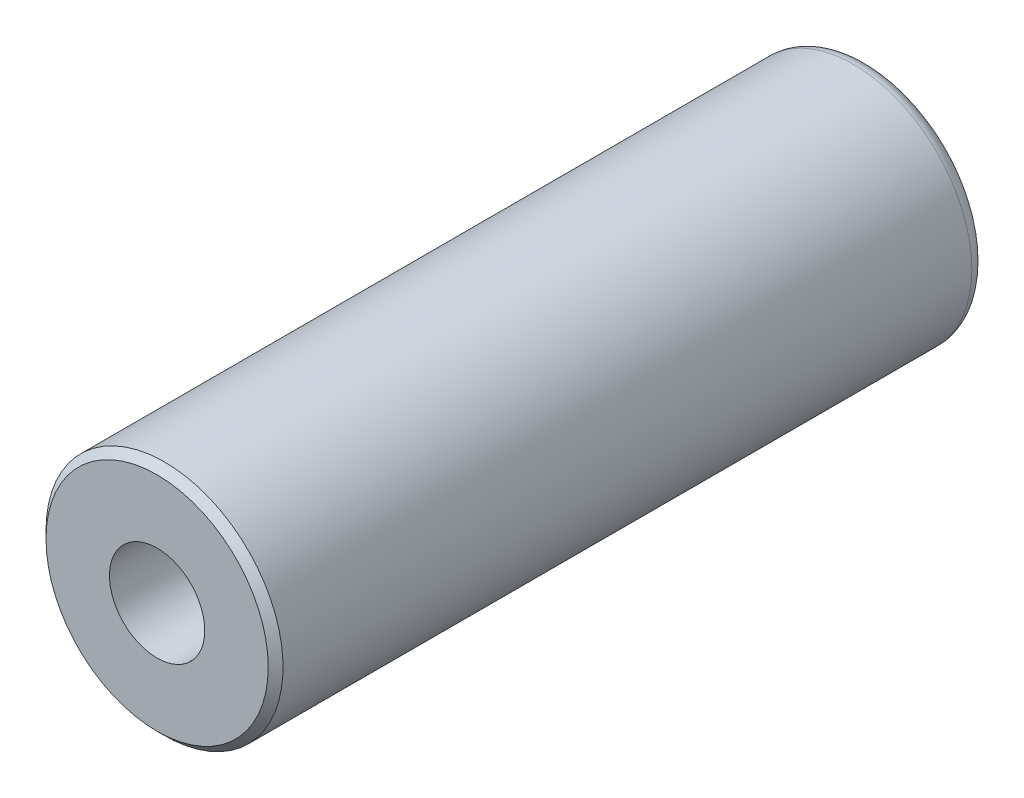
SolidWorks part; units mm, degrees
ref_plane "Front" through (0, 0, 0) normal (0, 0, 1) x (1, 0, 0)
ref_plane "Top" through (0, 0, 0) normal (0, 1, 0) x (1, 0, 0)
ref_plane "Right" through (0, 0, 0) normal (1, 0, 0) x (0, 0, -1)
sketch "Sketch1" plane through (0, 0, 0) normal (0, 0, 1) x (1, 0, 0)
  circle A0 centre (0, 0) radius 6.35
  dimension "D1" = 12.7
extrude "Extrude1" add sketch "Sketch1" along normal blind 38.1
hole_wizard "1/4-20 Tapped Hole1" positions "Sketch3" profile "Sketch2" tap size "1/4-20" standard "Ansi Inch"
sketch "Sketch3" plane through (0, 0, 38.1) normal (0, 0, 1) x (1, 0, 0)
  point P0 (0, 0)
sketch "Sketch2" plane through (0, 0, 38.1) normal (1, 0, 0) x (0, -1, 0)
  line L0 (0, 0) -> (0, 18.0438)
  line L1 (0, 18.0438) -> (2.5527, 16.51)
  line L2 (2.5527, 16.51) -> (2.5527, 0)
  line L5 (2.5527, 0) -> (0, 0)
  line L10 (0, 18.0438) -> (-2.5527, 16.51) construction
  line L11 (0, -6.35) -> (0, 107.95) construction
  dimension "Tap Drill Dia." = 5.1054
  dimension "Tap Drill Depth" = 16.51
  dimension "Drill Angle" = 118
cosmetic thread "Hole Thread1" parameters "D1"=12.7, "D2"=6.35
chamfer "Chamfer1" distance 0.3969 angle 45 1 edges at (6.35, 0, 38.1)
fillet "Fillet1" radius 0.7937 1 edges at (6.35, 0, 0)
